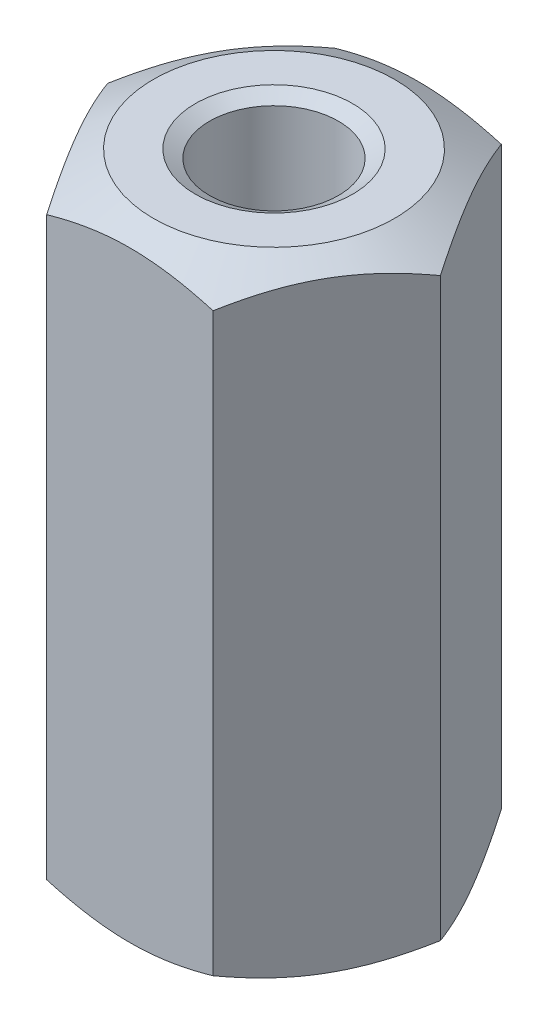
SolidWorks part; units mm, degrees
ref_plane "Ebene vorne" through (0, 0, 0) normal (0, 0, 1) x (1, 0, 0)
ref_plane "Ebene oben" through (0, 0, 0) normal (0, 1, 0) x (1, 0, 0)
ref_plane "Ebene rechts" through (0, 0, 0) normal (1, 0, 0) x (0, 0, -1)
sketch "Skizze2" plane through (0, 0, 0) normal (0, 1, 0) x (1, 0, 0)
  line L1 (3.1754, 0) -> (1.5877, 2.75)
  line L2 (1.5877, 2.75) -> (-1.5877, 2.75)
  line L3 (-1.5877, 2.75) -> (-3.1754, 0)
  line L4 (-3.1754, 0) -> (-1.5877, -2.75)
  line L5 (-1.5877, -2.75) -> (1.5877, -2.75)
  line L6 (1.5877, -2.75) -> (3.1754, 0)
  circle A0 centre (0, 0) radius 2.75 construction
  circle A1 centre (0, 0) radius 1.23
  dimension "D2" = 2.46
  dimension "D1" = 5.5
extrude "Aufsatz-Linear austragen1" add sketch "Skizze2" along normal mid plane 12
chamfer "Fase1" distance 0.27 angle 30 1 edges at (0, 6, 1.23)
chamfer "Fase2" distance 0.27 angle 30 1 edges at (0, -6, 1.23)
sketch "Skizze3" plane through (0, 0, 0) normal (0, 0, 1) x (1, 0, 0)
  line L0 (-2.3, 6) -> (-4.1169, 6)
  line L1 (-1.5877, 6) -> (-3.1754, 6) construction
  line L2 (-4.1169, 6) -> (-4.1169, 4.951)
  line L3 (-4.1169, 4.951) -> (-2.3, 6)
  line L4 (-2.3, -6) -> (-4.1169, -6)
  line L5 (-1.5877, -6) -> (-3.1754, -6) construction
  line L6 (-4.1169, -6) -> (-4.1169, -4.951)
  line L7 (-4.1169, -4.951) -> (-2.3, -6)
  dimension "D1" = 30
  dimension "D2" = 30
  dimension "D3" = 2.3
ref_axis "Achse1" through (0, 5.8441, 0) along (0, -1, 0)
revolve "Schnitt-Rotation1" cut sketch "Skizze3" angle 360 about axis through (0, 5.8441, 0) along (0, -1, 0)
